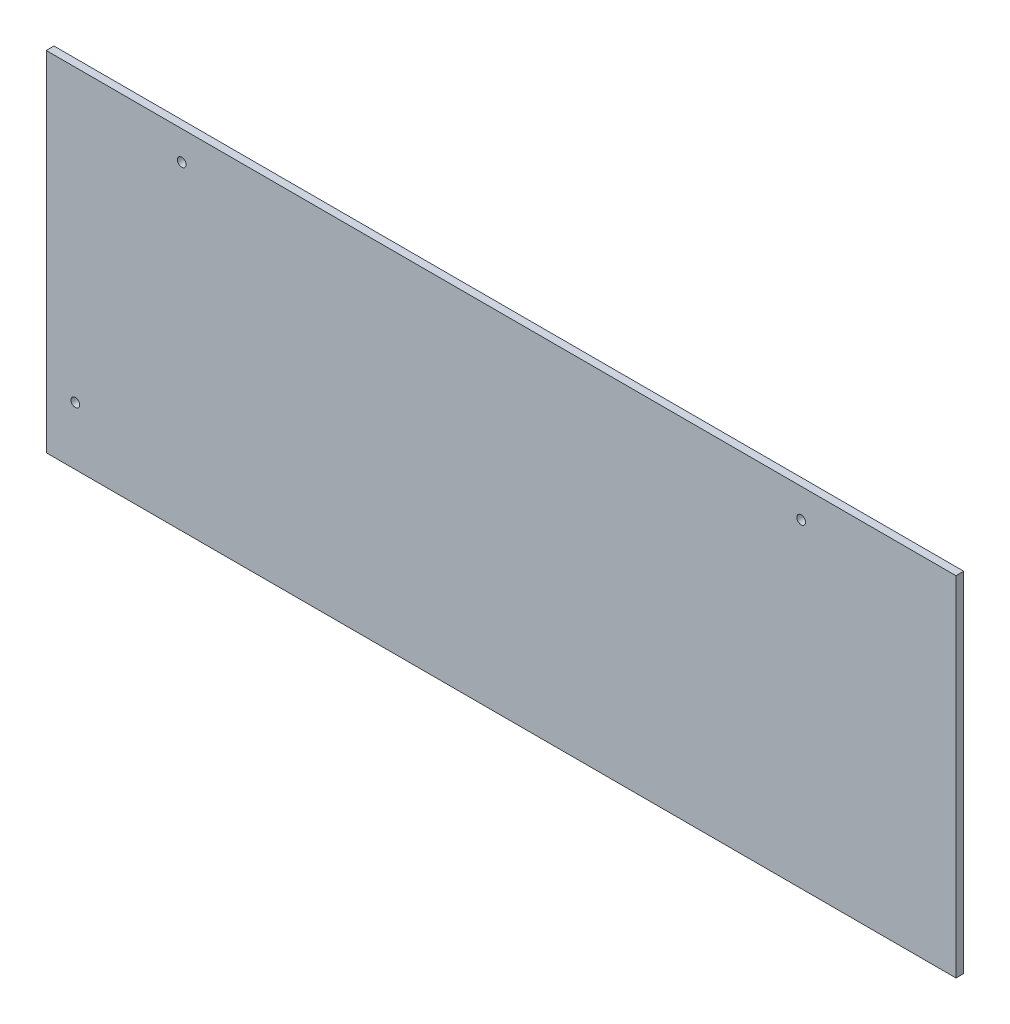
SolidWorks part; units mm, degrees
material "PC"
ref_plane "Front Plane" through (0, 0, 0) normal (0, 0, 1) x (1, 0, 0)
ref_plane "Top Plane" through (0, 0, 0) normal (0, 1, 0) x (1, 0, 0)
ref_plane "Right Plane" through (0, 0, 0) normal (1, 0, 0) x (0, 0, -1)
sketch "Sketch1" plane through (0, 0, 0) normal (0, 0, 1) x (1, 0, 0)
  line L1 (-235, 0) -> (235, 0)
  line L2 (-235, 0) -> (-235, -180)
  line L3 (-235, -180) -> (235, -180)
  line L4 (235, 0) -> (235, -180)
  dimension "D1" = 470
  dimension "D2" = 180
extrude "Boss-Extrude1" add sketch "Sketch1" along normal mid plane 4
sketch "Sketch2" plane through (0, 0, 2) normal (0, 0, 1) x (1, 0, 0)
  line L0 (-220, -150) -> (-220, -15) construction
  line L1 (235, -180) -> (235, 0) construction
  line L2 (155, -15) -> (-165, -15) construction
  line L3 (235, 0) -> (-235, 0) construction
  line L6 (-235, -180) -> (235, -180) construction
  line L7 (-165, -15) -> (-220, -15) construction
  line L8 (-235, 0) -> (-235, -180) construction
  circle A0 centre (-165, -15) radius 2.25
  circle A1 centre (155, -15) radius 2.25
  circle A2 centre (-220, -150) radius 2.25
  dimension "D1" = 4.5
  dimension "D2" = 15
  dimension "D3" = 80
  dimension "D4" = 320
  dimension "D5" = 15
  dimension "D6" = 30
extrude "Cut-Extrude1" cut sketch "Sketch2" against normal through all
